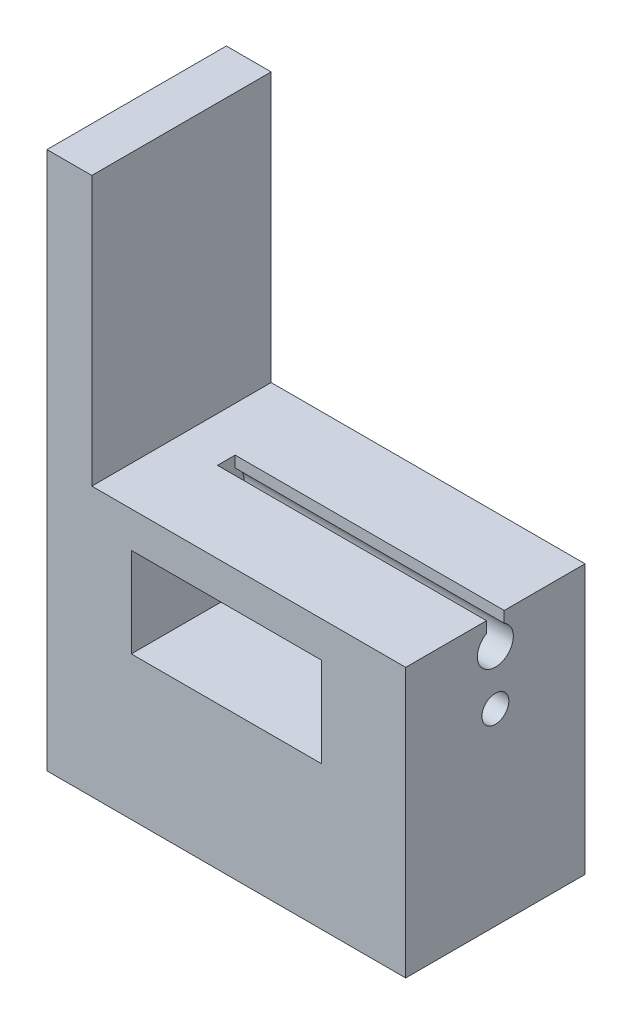
SolidWorks part; units mm, degrees
ref_plane "Front Plane" through (0, 0, 0) normal (0, 0, 1) x (1, 0, 0)
ref_plane "Top Plane" through (0, 0, 0) normal (0, 1, 0) x (1, 0, 0)
ref_plane "Right Plane" through (0, 0, 0) normal (1, 0, 0) x (0, 0, -1)
sketch "Sketch1" plane through (0, 0, 0) normal (0, 1, 0) x (1, 0, 0)
  line L1 (-25.4, 12.7) -> (25.4, 12.7)
  line L2 (-25.4, 12.7) -> (-25.4, -12.7)
  line L3 (-25.4, -12.7) -> (25.4, -12.7)
  line L4 (25.4, 12.7) -> (25.4, -12.7)
  line L5 (-25.4, 12.7) -> (25.4, -12.7) construction
  line L6 (-25.4, -12.7) -> (25.4, 12.7) construction
  point P0 (0, 0)
  dimension "D1" = 25.4
  dimension "D2" = 50.8
extrude "Boss-Extrude1" add sketch "Sketch1" along normal blind 38.1
sketch "Sketch2" plane through (0, 0, 12.7) normal (0, 0, 1) x (1, 0, 0)
  line L0 (0, 0) -> (0, 20.32) construction
  line L2 (-13.4546, 33.02) -> (13.4546, 33.02)
  line L3 (-13.4546, 33.02) -> (-13.4546, 20.32)
  line L4 (-13.4546, 20.32) -> (13.4546, 20.32)
  line L5 (13.4546, 33.02) -> (13.4546, 20.32)
  dimension "D1" = 12.7
  dimension "D2" = 20.32
  dimension "D3" = 26.9093
extrude "Cut-Extrude1" cut sketch "Sketch2" against normal through all both and the other way through all
sketch "Sketch3" plane through (-25.4, 0, 0) normal (-1, 0, 0) x (0, 0, 1)
  line L0 (0, 0) -> (0, 20.32) construction
  line L1 (0, 20.32) -> (0, 26.67) construction
  circle A0 centre (0, 26.67) radius 1.905
  dimension "D3" = 3.81
  dimension "D1" = 20.32
  dimension "D2" = 6.35
extrude "Cut-Extrude2" cut sketch "Sketch3" against normal through all both
sketch "Sketch4" plane through (0, 38.1, 0) normal (0, 1, 0) x (1, 0, 0)
  line L0 (25.4, 12.7) -> (-25.4, 12.7) construction
  line L1 (-25.4, -12.7) -> (-19.05, -12.7)
  line L2 (-25.4, -12.7) -> (-25.4, 12.7)
  line L3 (-25.4, 12.7) -> (-19.05, 12.7)
  line L4 (-19.05, -12.7) -> (-19.05, 12.7)
  line L5 (-25.4, -12.7) -> (25.4, -12.7) construction
  dimension "D1" = 6.35
extrude "Boss-Extrude2" add sketch "Sketch4" along normal blind 38.1
sketch "Sketch5" plane through (25.4, 0, 0) normal (1, 0, 0) x (0, 0, -1)
  line L0 (-12.7, 38.1) -> (12.7, 38.1) construction
  line L1 (-1.2546, 38.1) -> (1.2546, 38.1)
  line L2 (-1.2546, 38.1) -> (-1.2546, 36.5237)
  line L4 (1.2546, 38.1) -> (1.2546, 36.5237)
  line L5 (-1.2546, 38.1) -> (0.7993, 31.9029) construction
  line L6 (-0.7993, 31.9029) -> (1.2546, 38.1) construction
  arc A0 (-1.2546, 36.5237) -> (1.2546, 36.5237) centre (0, 34.3145) ccw
  dimension "D2" = 2.5406
  dimension "D1" = 2.5092
  dimension "D3" = 1.5763
extrude "Cut-Extrude3" cut sketch "Sketch5" against normal blind 38.1
